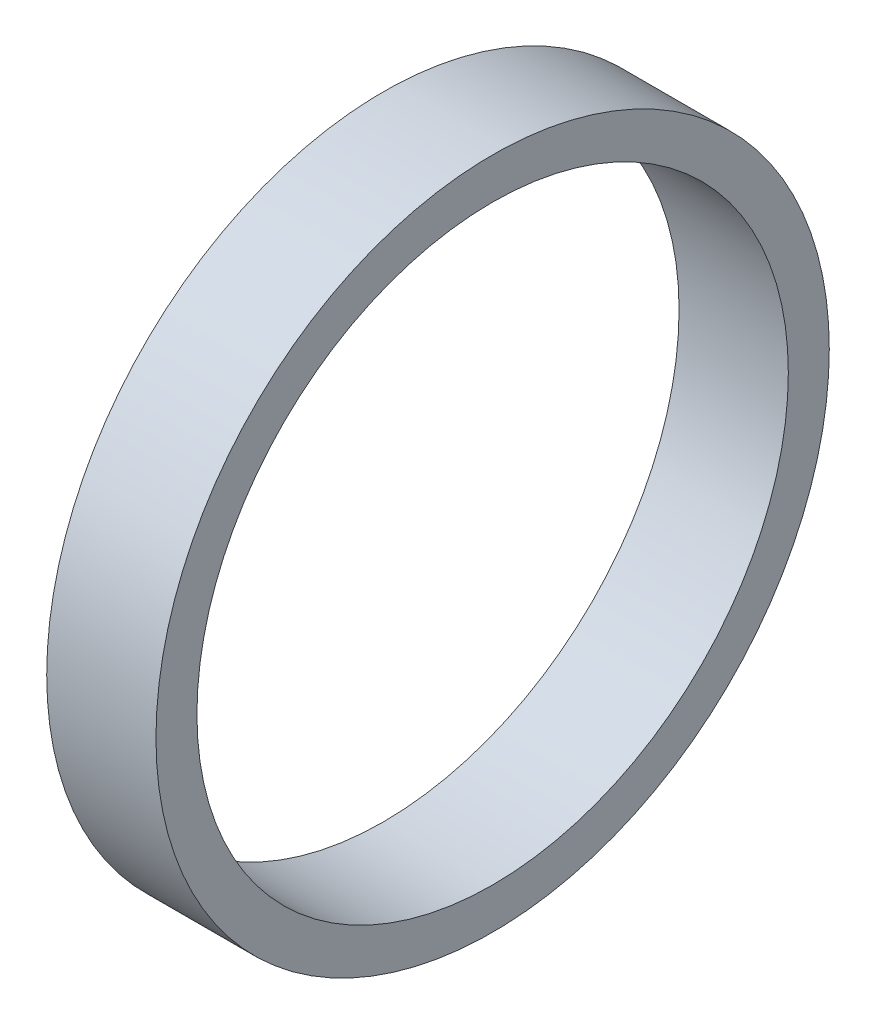
SolidWorks part; units mm, degrees
material "TPU 95A"
ref_plane "Front Plane" through (0, 0, 0) normal (1, 0, 0) x (0, 1, 0)
ref_plane "Top Plane" through (0, 0, 0) normal (0, 0, 1) x (0, 1, 0)
ref_plane "Right Plane" through (0, 0, 0) normal (0, 1, 0) x (-1, 0, 0)
sketch "Sketch1" plane through (0, 0, 0) normal (1, 0, 0) x (0, 1, 0)
  circle A0 centre (0, 0) radius 5.5
  circle A1 centre (0, 0) radius 6.262
  dimension "D1" = 11
  dimension "D2" = 12.524
extrude "Boss-Extrude1" add sketch "Sketch1" along normal blind 2.032
equation "\"D1@Sketch1\"=11mm"
equation "\"D2@Sketch1\"=11mm+0.06"
